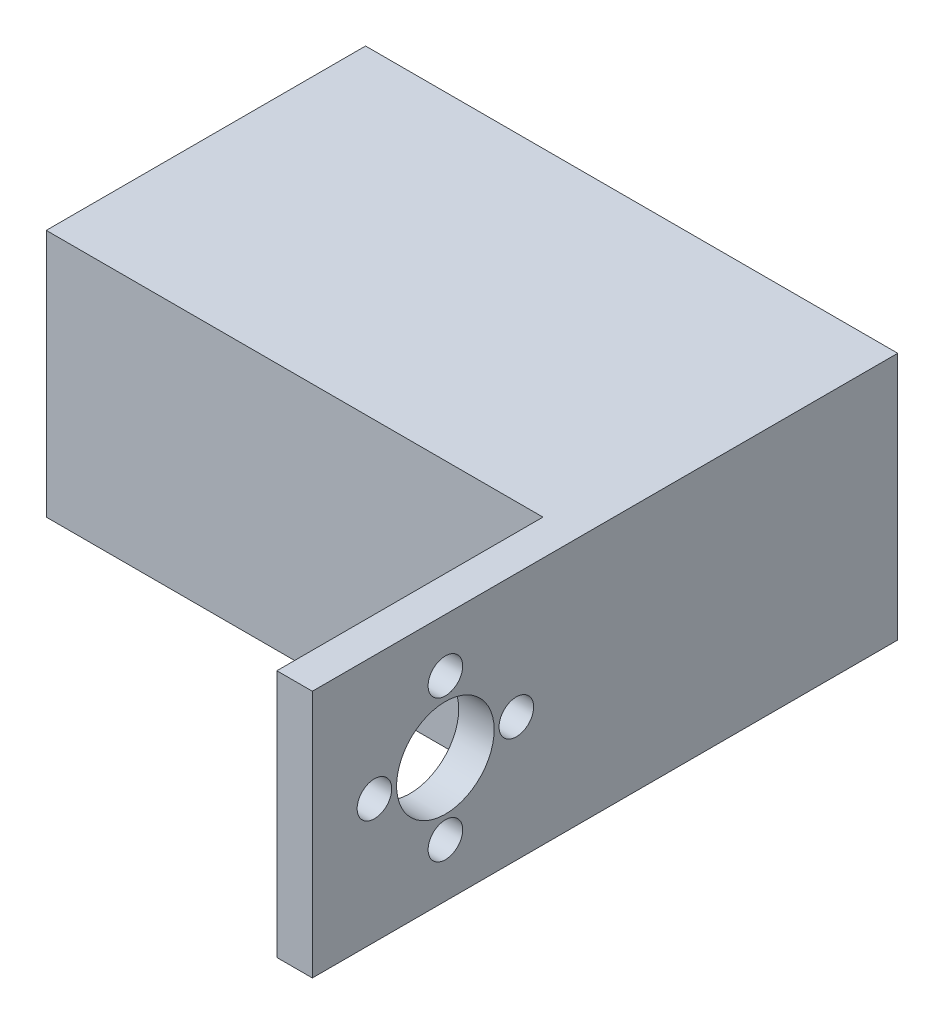
SolidWorks part; units mm, degrees
ref_plane "Front Plane" through (0, 0, 0) normal (0, 0, 1) x (1, 0, 0)
ref_plane "Top Plane" through (0, 0, 0) normal (0, 1, 0) x (1, 0, 0)
ref_plane "Right Plane" through (0, 0, 0) normal (1, 0, 0) x (0, 0, -1)
sketch "Sketch1" plane through (0, 0, 0) normal (0, 0, 1) x (1, 0, 0)
  line L0 (-10, 4) -> (50, 4)
  line L1 (0, 0) -> (40, 0)
  line L2 (0, 0) -> (0, -20)
  line L3 (0, -20) -> (40, -20)
  line L4 (40, 0) -> (40, -20)
  line L5 (50, 4) -> (50, -24)
  line L6 (-10, -24) -> (50, -24)
  line L7 (-10, 4) -> (-10, -24)
  point P11 (20, 4)
  point P12 (20, 0)
  dimension "D1" = 40
  dimension "D2" = 20
  dimension "D3" = 4
  dimension "D4" = 4
  dimension "D5" = 60
extrude "Boss-Extrude1" add sketch "Sketch1" along normal blind 32
sketch "Sketch2" plane through (0, 0, 32) normal (0, 0, 1) x (1, 0, 0)
  line L0 (-10, -24) -> (50, -24) construction
  line L1 (50, -24) -> (50, 4) construction
  line L2 (50, 4) -> (-10, 4) construction
  line L3 (-10, 4) -> (-10, -24) construction
  line L4 (-10, -24) -> (50, -24)
  line L5 (50, -24) -> (50, 4)
  line L6 (50, 4) -> (-10, 4)
  line L7 (-10, 4) -> (-10, -24)
extrude "Boss-Extrude2" add sketch "Sketch2" along normal blind 4
sketch "Sketch3" plane through (50, 0, 0) normal (1, 0, 0) x (0, 0, -1)
  line L0 (-36, -24) -> (0, -24) construction
  line L1 (-36, 4) -> (-66, 4)
  line L2 (-36, 4) -> (-36, -24)
  line L3 (-36, -24) -> (-66, -24)
  line L4 (-66, 4) -> (-66, -24)
  circle A0 centre (-51, -10) radius 5.5
  point P9 (-51, 4)
  point P10 (-66, -10)
  dimension "D2" = 11
  dimension "D1" = 30
extrude "Boss-Extrude3" add sketch "Sketch3" against normal blind 4
sketch "Sketch4" plane through (50, 0, 0) normal (1, 0, 0) x (0, 0, -1)
  circle A0 centre (-51, -18) radius 1.95
  circle A1 centre (-59, -10) radius 1.95
  circle A2 centre (-43, -10) radius 1.95
  circle A3 centre (-51, -2) radius 1.95
extrude "Cut-Extrude1" cut sketch "Sketch4" against normal up to surface (4 mm away) up to face at (46, -10, 45.5)
sketch "Sketch5" plane through (0, 0, 0) normal (0, 0, -1) x (-1, 0, 0)
  circle A0 centre (-44.4, -5) radius 2.2
  circle A1 centre (-44.4, -15) radius 2.2
  circle A2 centre (4.4, -5) radius 2.2
  circle A3 centre (4.4, -15) radius 2.2
extrude "Cut-Extrude2" cut sketch "Sketch5" against normal blind 15
